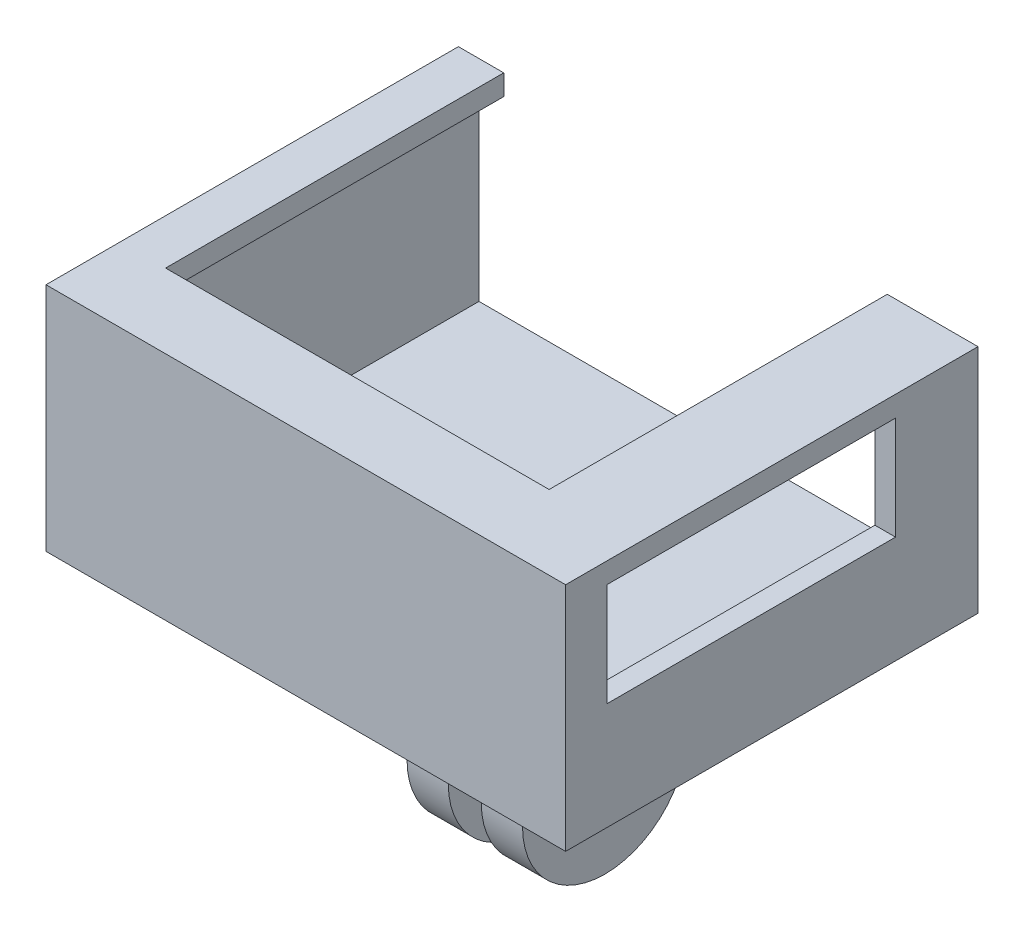
SolidWorks part; units mm, degrees
ref_plane "Front Plane" through (0, 0, 0) normal (0, 0, 1) x (1, 0, 0)
ref_plane "Top Plane" through (0, 0, 0) normal (0, 1, 0) x (1, 0, 0)
ref_plane "Right Plane" through (0, 0, 0) normal (1, 0, 0) x (0, 0, -1)
sketch "Sketch1" plane through (0, 0, 0) normal (0, 1, 0) x (1, 0, 0)
  line L1 (-28.7752, 15.9549) -> (34.2248, 15.9549)
  line L2 (-28.7752, 15.9549) -> (-28.7752, -34.0451)
  line L3 (-28.7752, -34.0451) -> (34.2248, -34.0451)
  line L4 (34.2248, 15.9549) -> (34.2248, -34.0451)
  dimension "D1" = 63
  dimension "D2" = 50
extrude "Boss-Extrude1" add sketch "Sketch1" along normal blind 28
sketch "Sketch2" plane through (0, 0, 34.0451) normal (0, 0, 1) x (1, 0, 0)
  line L1 (-28.2752, 22.5) -> (31.7248, 22.5)
  line L2 (-28.2752, 22.5) -> (-28.2752, 2.5)
  line L3 (-28.2752, 2.5) -> (31.7248, 2.5)
  line L4 (31.7248, 22.5) -> (31.7248, 2.5)
  line L6 (55, 0) -> (-55, 0) construction
  line L8 (34.2248, 28) -> (34.2248, 0) construction
  dimension "D1" = 60
  dimension "D2" = 20
  dimension "D3" = 2.5
  dimension "D4" = 2.5
extrude "Cut-Extrude1" cut sketch "Sketch2" against normal through all from offset 5 offset against normal yes
sketch "Sketch3" plane through (0, 28, 0) normal (0, 1, 0) x (1, 0, 0)
  line L0 (34.2248, 15.9549) -> (-28.7752, 15.9549) construction
  line L1 (-28.7752, 15.9549) -> (11.2248, 15.9549)
  line L2 (-28.7752, 15.9549) -> (-28.7752, -19.0451)
  line L3 (-28.7752, -19.0451) -> (11.2248, -19.0451)
  line L4 (11.2248, 15.9549) -> (11.2248, -19.0451)
  dimension "D1" = 35
  dimension "D2" = 40
extrude "Cut-Extrude2" cut sketch "Sketch3" against normal up to surface (25.5 mm away) up to face at (1.7248, 2.5, 6.5451)
sketch "Sketch4" plane through (0, 28, 0) normal (0, 1, 0) x (1, 0, 0)
  line L0 (11.2248, -19.0451) -> (11.2248, 15.9549) construction
  line L1 (11.2248, 5.9549) -> (34.2248, 5.9549)
  line L2 (11.2248, 5.9549) -> (11.2248, -19.0451)
  line L3 (11.2248, -19.0451) -> (34.2248, -19.0451)
  line L4 (34.2248, 5.9549) -> (34.2248, -19.0451)
  line L5 (34.2248, -34.0451) -> (34.2248, 15.9549) construction
  line L6 (34.2248, 15.9549) -> (11.2248, 15.9549) construction
  line L7 (-28.7752, -34.0451) -> (34.2248, -34.0451) construction
  dimension "D1" = 10
  dimension "D2" = 15
extrude "Cut-Extrude3" cut sketch "Sketch4" against normal up to surface (25.5 mm away) up to face at (-8.4419, 2.5, 10.7117)
sketch "Sketch5" plane through (0, 0, 19.0451) normal (0, 0, -1) x (-1, 0, 0)
  line L0 (28.7752, 28) -> (-34.2248, 28) construction
  line L1 (28.7752, 2.5) -> (26.2752, 2.5)
  line L2 (28.7752, 2.5) -> (28.7752, 28)
  line L3 (28.7752, 28) -> (26.2752, 28)
  line L4 (26.2752, 2.5) -> (26.2752, 28)
  dimension "D1" = 2.5
extrude "Boss-Extrude2" add sketch "Sketch5" along normal up to surface (35 mm away) up to face at (12.0998, 13.25, -15.9549)
sketch "Sketch6" plane through (34.2248, 0, 0) normal (1, 0, 0) x (0, 0, -1)
  line L1 (-34.0451, 28) -> (-4.0451, 28)
  line L2 (-34.0451, 28) -> (-34.0451, 13)
  line L3 (-34.0451, 13) -> (-4.0451, 13)
  line L4 (-4.0451, 28) -> (-4.0451, 13)
  dimension "D1" = 15
  dimension "D2" = 30
extrude "Cut-Extrude4" cut sketch "Sketch6" against normal up to surface (2.5 mm away) up to face at (31.7248, 12.5, 24.0451)
sketch "Sketch7" plane through (0, 0, 19.0451) normal (0, 0, -1) x (-1, 0, 0)
  line L1 (-31.7248, 2.5) -> (-34.2248, 2.5)
  line L2 (-31.7248, 2.5) -> (-31.7248, 13)
  line L3 (-31.7248, 13) -> (-34.2248, 13)
  line L4 (-34.2248, 2.5) -> (-34.2248, 13)
extrude "Boss-Extrude3" add sketch "Sketch7" along normal up to surface (25 mm away) up to face at (25.7248, 17.6667, -5.9549)
sketch "Sketch8" plane through (31.7248, 0, 0) normal (1, 0, 0) x (0, 0, -1)
  line L1 (-29.0451, 13) -> (-34.0451, 13)
  line L2 (-29.0451, 13) -> (-29.0451, 28)
  line L3 (-29.0451, 28) -> (-34.0451, 28)
  line L4 (-34.0451, 13) -> (-34.0451, 28)
extrude "Boss-Extrude4" add sketch "Sketch8" along normal up to surface (2.5 mm away) up to face at (34.2248, 13.6667, 4.0451)
sketch "Sketch9" plane through (31.7248, 0, 0) normal (1, 0, 0) x (0, 0, -1)
  line L1 (-19.0451, 28) -> (-29.0451, 28)
  line L2 (-19.0451, 28) -> (-19.0451, 22.5)
  line L3 (-19.0451, 22.5) -> (-29.0451, 22.5)
  line L4 (-29.0451, 28) -> (-29.0451, 22.5)
extrude "Boss-Extrude5" add sketch "Sketch9" along normal up to surface (2.5 mm away) up to face at (34.2248, 17.25, 10.2951)
sketch "Sketch11" plane through (0, 0, 0) normal (1, 0, 0) x (0, 0, -1)
  line L0 (-34.0451, 28) -> (-34.0451, 0) construction
  line L2 (55, 0) -> (-55, 0) construction
  line L3 (0.9549, 0) -> (-19.0451, 0)
  line L4 (0.9549, 0) -> (0.9549, -15)
  line L6 (-19.0451, 0) -> (-19.0451, -15)
  line L7 (15.9549, 28) -> (15.9549, 0) construction
  arc A1 (0.9549, -15) -> (-19.0451, -15) centre (-9.0451, -15) cw
  dimension "D1" = 15
  dimension "D2" = 15
  dimension "D3" = 15
extrude "Boss-Extrude6" add sketch "Sketch11" along normal blind 20
sketch "Sketch12" plane through (0, 0, 0) normal (-1, 0, 0) x (0, 0, 1)
  line L0 (19.0451, -15) -> (19.0451, 0)
  line L1 (55, 0) -> (-55, 0) construction
  line L2 (19.0451, 0) -> (-0.9549, 0)
  line L3 (-0.9549, 0) -> (-0.9549, -15)
  arc A0 (19.0451, -15) -> (-0.9549, -15) centre (9.0451, -15) cw
extrude "Cut-Extrude6" cut sketch "Sketch12" against normal blind 4 from offset 5 offset against normal yes
sketch "Sketch13" plane through (0, 0, 0) normal (1, 0, 0) x (0, 0, -1)
  line L0 (-19.0451, -15) -> (-19.0451, 0)
  line L1 (55, 0) -> (-55, 0) construction
  line L2 (-19.0451, -15) -> (-19.0451, 0) construction
  line L3 (-19.0451, 0) -> (0.9549, 0)
  line L4 (0.9549, 0) -> (0.9549, -15)
  arc A0 (-19.0451, -15) -> (0.9549, -15) centre (-9.0451, -15) ccw
sketch "Sketch14" plane through (9, 0, 0) normal (-1, 0, 0) x (0, 0, 1)
  line L0 (19.0451, -15) -> (19.0451, 0)
  line L1 (19.0451, 0) -> (-0.9549, 0)
  line L2 (-0.9549, 0) -> (-0.9549, -15)
  arc A0 (19.0451, -15) -> (-0.9549, -15) centre (9.0451, -15) cw
extrude "Cut-Extrude8" cut sketch "Sketch14" against normal blind 3 from offset 5 offset against normal yes
sketch "Sketch15" plane through (17, 0, 0) normal (-1, 0, 0) x (0, 0, 1)
  line L0 (19.0451, -15) -> (19.0451, 0)
  line L1 (19.0451, 0) -> (-0.9549, 0)
  line L2 (-0.9549, 0) -> (-0.9549, -15)
  arc A0 (19.0451, -15) -> (-0.9549, -15) centre (9.0451, -15) cw
extrude "Cut-Extrude9" cut sketch "Sketch15" against normal through all
sketch "Sketch16" plane through (0, 0, 19.0451) normal (0, 0, -1) x (-1, 0, 0)
  line L1 (26.2752, 22.5) -> (-34.2248, 22.5)
  line L2 (26.2752, 22.5) -> (26.2752, 28)
  line L3 (26.2752, 28) -> (-34.2248, 28)
  line L4 (-34.2248, 22.5) -> (-34.2248, 28)
extrude "Cut-Extrude10" cut sketch "Sketch16" against normal blind 9
sketch "Sketch17" plane through (11.2248, 0, 0) normal (-1, 0, 0) x (0, 0, 1)
  line L1 (-15.9549, 22.5) -> (-5.9549, 22.5)
  line L2 (-15.9549, 22.5) -> (-15.9549, 28)
  line L3 (-15.9549, 28) -> (-5.9549, 28)
  line L4 (-5.9549, 22.5) -> (-5.9549, 28)
extrude "Cut-Extrude11" cut sketch "Sketch17" against normal blind 18.5
sketch "Sketch18" plane through (0, 0, -5.9549) normal (0, 0, 1) x (1, 0, 0)
  line L1 (34.2248, 28) -> (29.7248, 28)
  line L2 (34.2248, 28) -> (34.2248, 22.5)
  line L3 (34.2248, 22.5) -> (29.7248, 22.5)
  line L4 (29.7248, 28) -> (29.7248, 22.5)
extrude "Boss-Extrude7" add sketch "Sketch18" along normal up to surface (34 mm away) up to face at (3.9748, 25.25, 28.0451)
sketch "Sketch23" plane through (0, 2.5, 0) normal (0, 1, 0) x (1, 0, 0)
  line L1 (-26.2752, 15.9549) -> (31.7248, 15.9549)
  line L2 (-26.2752, 15.9549) -> (-26.2752, -29.0451)
  line L3 (-26.2752, -29.0451) -> (31.7248, -29.0451)
  line L4 (31.7248, 15.9549) -> (31.7248, -29.0451)
extrude "Cut-Extrude14" cut sketch "Sketch23" along normal blind 23
sketch "Sketch24" plane through (0, 22.5, 0) normal (0, -1, 0) x (1, 0, 0)
  line L1 (31.7248, -5.9549) -> (34.2248, -5.9549)
  line L2 (31.7248, -5.9549) -> (31.7248, 29.0451)
  line L3 (31.7248, 29.0451) -> (34.2248, 29.0451)
  line L4 (34.2248, -5.9549) -> (34.2248, 29.0451)
extrude "Cut-Extrude15" cut sketch "Sketch24" against normal blind 3
sketch "Sketch25" plane through (29.7248, 0, 0) normal (-1, 0, 0) x (0, 0, 1)
  line L1 (-15.9549, 25.5) -> (28.0451, 25.5)
  line L2 (-15.9549, 25.5) -> (-15.9549, 28)
  line L3 (-15.9549, 28) -> (28.0451, 28)
  line L4 (28.0451, 25.5) -> (28.0451, 28)
extrude "Boss-Extrude9" add sketch "Sketch25" against normal blind 3 from surface at 56 starting at face at (-26.2752, 19.625, 15.0451)
sketch "Sketch26" plane through (-28.7752, 0, 0) normal (-1, 0, 0) x (0, 0, 1)
  line L1 (19.0451, 2.5) -> (29.0451, 2.5)
  line L2 (19.0451, 2.5) -> (19.0451, 22.5)
  line L3 (19.0451, 22.5) -> (29.0451, 22.5)
  line L4 (29.0451, 2.5) -> (29.0451, 22.5)
extrude "Boss-Extrude10" add sketch "Sketch26" against normal up to surface (2.5 mm away) up to face at (-26.2752, 16.8333, 10.7117)
sketch "Sketch27" plane through (29.7248, 0, 0) normal (-1, 0, 0) x (0, 0, 1)
  line L1 (-15.9549, 25.5) -> (28.0451, 25.5)
  line L2 (-15.9549, 25.5) -> (-15.9549, 28)
  line L3 (-15.9549, 28) -> (28.0451, 28)
  line L4 (28.0451, 25.5) -> (28.0451, 28)
extrude "Boss-Extrude11" add sketch "Sketch27" along normal blind 6.5
sketch "Sketch28" plane through (0, 0, 28.0451) normal (0, 0, -1) x (-1, 0, 0)
  line L1 (-23.2248, 25.5) -> (23.2752, 25.5)
  line L2 (-23.2248, 25.5) -> (-23.2248, 28)
  line L3 (-23.2248, 28) -> (23.2752, 28)
  line L4 (23.2752, 25.5) -> (23.2752, 28)
extrude "Boss-Extrude12" add sketch "Sketch28" along normal blind 7
sketch "Sketch29" plane through (0, 0, 21.0451) normal (0, 0, -1) x (-1, 0, 0)
  line L0 (23.2752, 28) -> (-23.2248, 28) construction
  line L1 (23.2752, 25.5) -> (-23.2248, 25.5)
  line L2 (23.2752, 25.5) -> (23.2752, 28)
  line L3 (23.2752, 28) -> (-23.2248, 28)
  line L4 (-23.2248, 25.5) -> (-23.2248, 28)
extrude "Cut-Extrude16" cut sketch "Sketch29" against normal blind 4
